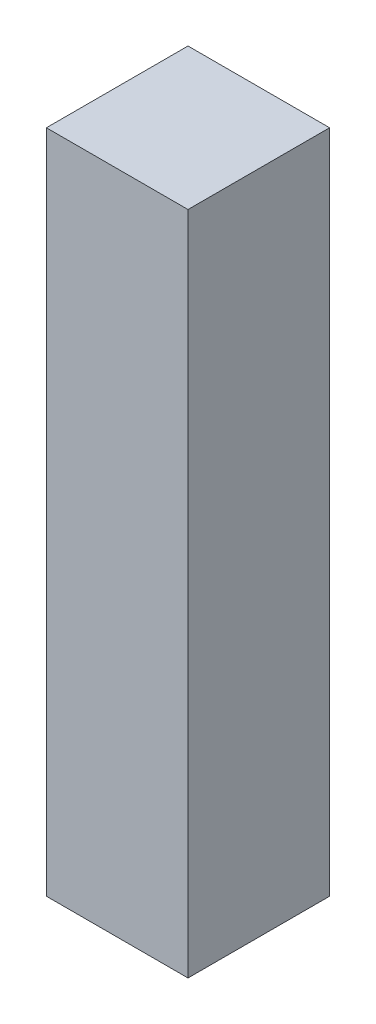
SolidWorks part; units mm, degrees
ref_plane "Front Plane" through (0, 0, 0) normal (0, 0, 1) x (1, 0, 0)
ref_plane "Top Plane" through (0, 0, 0) normal (0, 1, 0) x (1, 0, 0)
ref_plane "Right Plane" through (0, 0, 0) normal (1, 0, 0) x (0, 0, -1)
sketch "Sketch1" plane through (0, 0, 0) normal (0, 1, 0) x (1, 0, 0)
  line L1 (100, -100) -> (-100, -100)
  line L2 (100, -100) -> (100, 100)
  line L3 (100, 100) -> (-100, 100)
  line L4 (-100, -100) -> (-100, 100)
  line L5 (100, -100) -> (-100, 100) construction
  line L6 (100, 100) -> (-100, -100) construction
  point P0 (0, 0)
  dimension "D1" = 200
  dimension "D2" = 200
extrude "Boss-Extrude1" add sketch "Sketch1" against normal blind 940
equation "\"L\"= 940"
